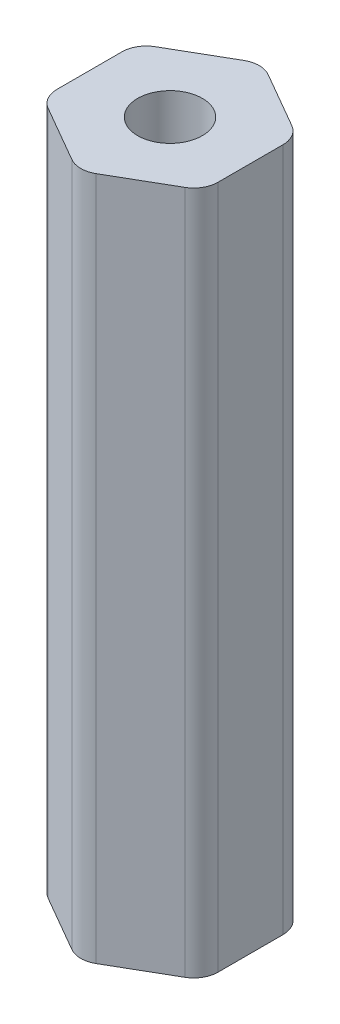
SolidWorks part; units mm, degrees
ref_plane "Front Plane" through (0, 0, 0) normal (0, 0, 1) x (1, 0, 0)
ref_plane "Top Plane" through (0, 0, 0) normal (0, 1, 0) x (1, 0, 0)
ref_plane "Right Plane" through (0, 0, 0) normal (1, 0, 0) x (0, 0, -1)
sketch "Sketch1" plane through (0, 0, 0) normal (0, 1, 0) x (1, 0, 0)
  line L1 (0, 7.3323) -> (-6.35, 3.6662)
  line L2 (-6.35, 3.6662) -> (-6.35, -3.6662)
  line L3 (-6.35, -3.6662) -> (0, -7.3323)
  line L4 (0, -7.3323) -> (6.35, -3.6662)
  line L5 (6.35, -3.6662) -> (6.35, 3.6662)
  line L6 (6.35, 3.6662) -> (0, 7.3323)
  circle A0 centre (0, 0) radius 6.35 construction
  circle A1 centre (0, 0) radius 2.5527
  dimension "D2" = 5.1054
  dimension "D1" = 12.7
extrude "Boss-Extrude1" add sketch "Sketch1" along normal blind 53.975
fillet "Fillet1" radius 1.905 6 edges at (-6.35, 26.9875, -3.6662) (0, 26.9875, -7.3323) (6.35, 26.9875, -3.6662) (-6.35, 26.9875, 3.6662) (6.35, 26.9875, 3.6662) (0, 26.9875, 7.3323)
equation "\"length\" = 2.125"
equation "\"D1@Boss-Extrude1\"=\"length\""
